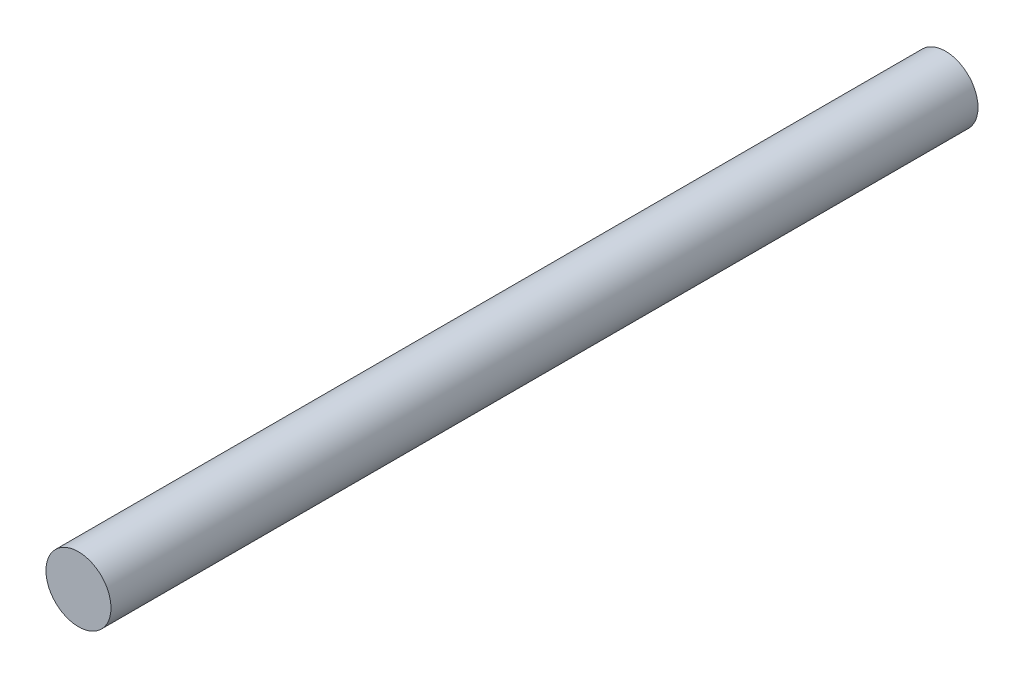
SolidWorks part; units mm, degrees
material "Alloy Steel"
ref_plane "Front Plane" through (0, 0, 0) normal (0, 0, 1) x (1, 0, 0)
ref_plane "Top Plane" through (0, 0, 0) normal (0, 1, 0) x (1, 0, 0)
ref_plane "Right Plane" through (0, 0, 0) normal (1, 0, 0) x (0, 0, -1)
sketch "Sketch1" plane through (0, 0, 0) normal (0, 0, 1) x (1, 0, 0)
  circle A0 centre (0, 0) radius 4.7625
  dimension "D1" = 9.525
extrude "Boss-Extrude1" add sketch "Sketch1" against normal blind 127
